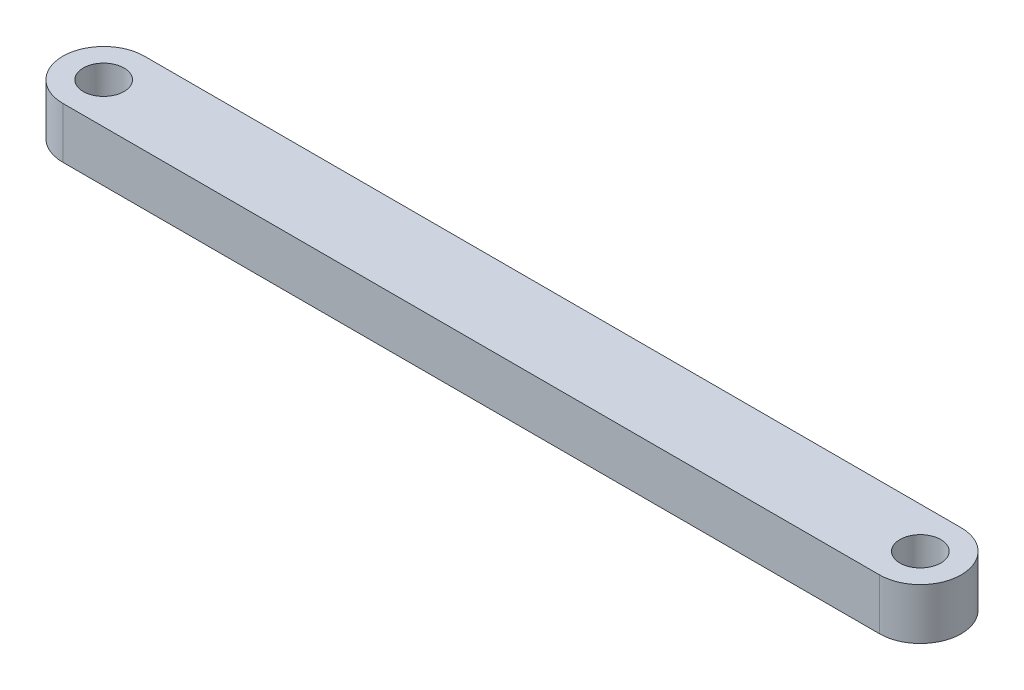
SolidWorks part; units mm, degrees
ref_plane "Front Plane" through (0, 0, 0) normal (0, 0, 1) x (1, 0, 0)
ref_plane "Top Plane" through (0, 0, 0) normal (0, 1, 0) x (1, 0, 0)
ref_plane "Right Plane" through (0, 0, 0) normal (1, 0, 0) x (0, 0, -1)
sketch "Sketch1" plane through (0, 0, 0) normal (0, 1, 0) x (1, 0, 0)
  line L1 (-20, -2) -> (20, -2)
  line L2 (-20, -2) -> (-20, 2)
  line L3 (-20, 2) -> (20, 2)
  line L4 (20, -2) -> (20, 2)
  line L5 (-20, -2) -> (20, 2) construction
  line L6 (-20, 2) -> (20, -2) construction
  circle A0 centre (20, 0) radius 2
  circle A1 centre (-20, 0) radius 2
  point P0 (0, 0)
  dimension "D1" = 4
  dimension "D2" = 40
extrude "Boss-Extrude1" add sketch "Sketch1" along normal blind 2.5 contours L2 A1 | L2 A1 | A1 L1 A0 L3 | L4 A0 | L4 A0
sketch "Sketch2" plane through (0, 0, 0) normal (0, 1, 0) x (1, 0, 0)
  arc A0 (20, -2) -> (20, 2) centre (20, 0) ccw construction
  arc A1 (20, -2) -> (20, 2) centre (20, 0) ccw
  circle A2 centre (20, 0) radius 1
  arc A3 (-20, 2) -> (-20, -2) centre (-20, 0) ccw construction
  arc A4 (-20, 2) -> (-20, -2) centre (-20, 0) ccw
  circle A5 centre (-20, 0) radius 1
  dimension "D1" = 2
extrude "Cut-Extrude1" cut sketch "Sketch2" along normal through all contours A2 | A5
